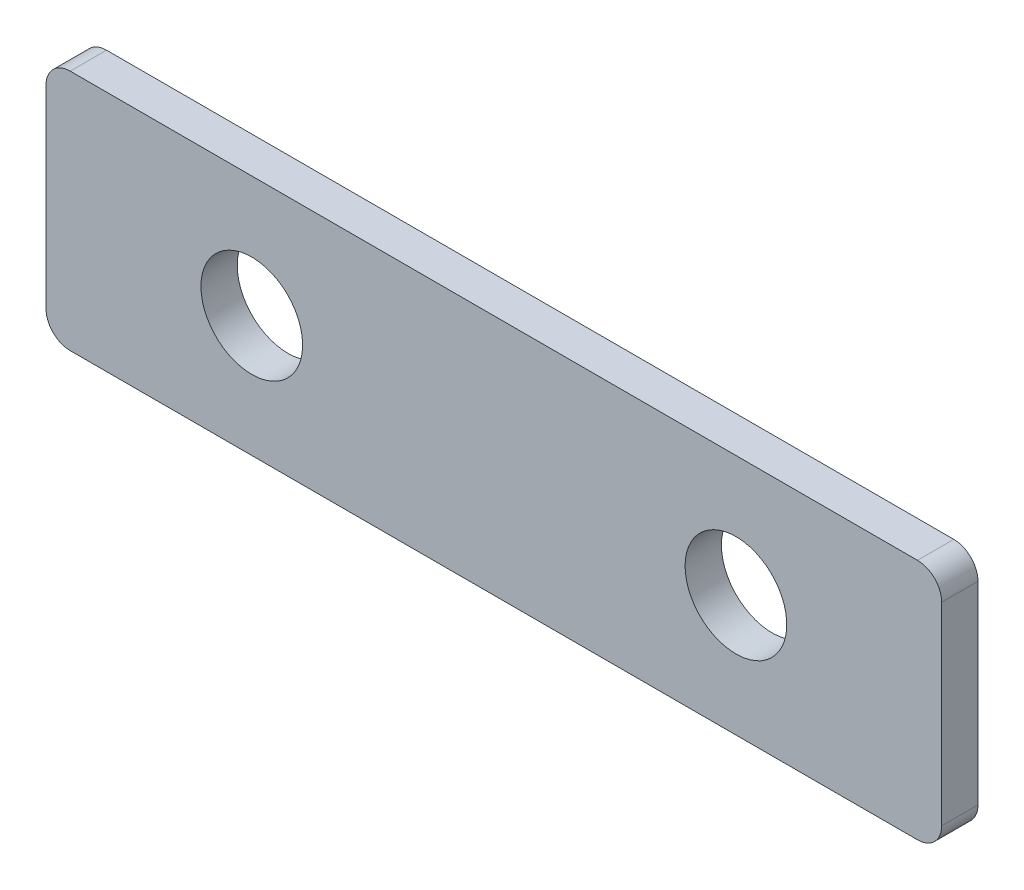
SolidWorks part; units mm, degrees
ref_plane "Top" through (0, 0, 0) normal (0, 0, 1) x (1, 0, 0)
ref_plane "Front" through (0, 0, 0) normal (0, 1, 0) x (1, 0, 0)
ref_plane "Right" through (0, 0, 0) normal (1, 0, 0) x (0, 0, -1)
sketch "Sketch1" plane through (0, 0, 0) normal (0, 0, 1) x (1, 0, 0)
  line L0 (0, 0) -> (18.5, 0) construction
  line L1 (-17.5, -5) -> (17.5, -5)
  line L2 (-18.5, -4) -> (-18.5, 4)
  line L3 (-17.5, 5) -> (17.5, 5)
  line L4 (18.5, -4) -> (18.5, 4)
  line L5 (-18.5, -5) -> (18.5, 5) construction
  line L6 (-18.5, 5) -> (18.5, -5) construction
  circle A0 centre (-10, 0) radius 2.1
  circle A1 centre (10, 0) radius 2.1
  arc A2 (17.5, 5) -> (18.5, 4) centre (17.5, 4) cw
  arc A3 (18.5, -4) -> (17.5, -5) centre (17.5, -4) cw
  arc A4 (-17.5, -5) -> (-18.5, -4) centre (-17.5, -4) cw
  arc A5 (-18.5, 4) -> (-17.5, 5) centre (-17.5, 4) cw
  point P1 (0, 0)
  dimension "D5" = 1
  dimension "D6" = 4.2
  dimension "D1" = 37
  dimension "D2" = 10
  dimension "D3" = 10
  dimension "D4" = 10
extrude "Boss-Extrude1" add sketch "Sketch1" along normal blind 1.5
move or copy body "Body-Move/Copy1" [suppressed] bodies to move or copy 101
equation "\"M2x0.4_Close_Hole\"= 2.2"
equation "\"M2.5x0.45_Close_Hole\"= 2.7"
equation "\"M3x0.5_Close_Hole\"= 3.2"
equation "\"M4x0.7_Close_Hole\"= 4.3"
equation "\"M5x0.8_Close_Hole\"= 5.3"
equation "\"M6x1_Close_Hole\"= 6.3"
equation "\"M7x1_Close_Hole\"= 7.4"
equation "\"M8x1.25_Close_Hole\"= 8.4"
equation "\"M2x0.4_Tap_Hole_75\"= 1.6"
equation "\"M3x0.5_Tap_Hole_75\"= 2.5"
equation "\"M4x0.7_Tap_Hole_75\"= 3.3"
equation "\"M5x0.8_Tap_Hole_75\"= 4.2"
equation "\"M6x1_Tap_Hole_75\"= 5"
equation "\"M7x1_Tap_Hole_75\"= 6"
equation "\"M8x1.25_Tap_Hole_75\"= 6.8"
equation "\"D6@Sketch1\"=\"M5x0.8_Tap_Hole_75\""
